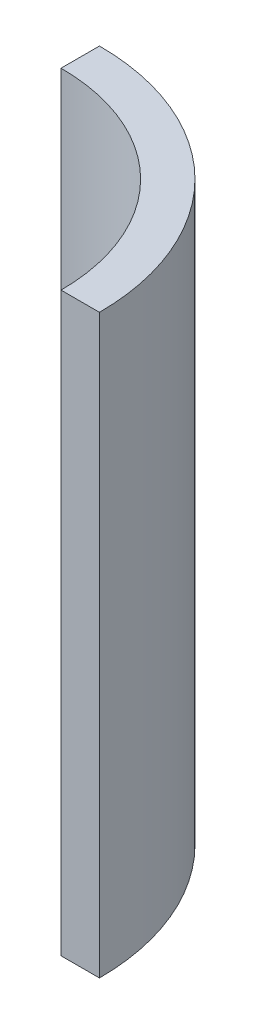
SolidWorks part; units mm, degrees
ref_plane "Front Plane" through (0, 0, 0) normal (0, 0, 1) x (1, 0, 0)
ref_plane "Top Plane" through (0, 0, 0) normal (0, 1, 0) x (1, 0, 0)
ref_plane "Right Plane" through (0, 0, 0) normal (1, 0, 0) x (0, 0, -1)
sketch "Sketch1" plane through (0, 0, 0) normal (0, 1, 0) x (1, 0, 0)
  arc A0 (50, 0) -> (0, 50) centre (0, 0) ccw
extrude "Extrude-Thin1" add sketch "Sketch1" along normal blind 150 thin
